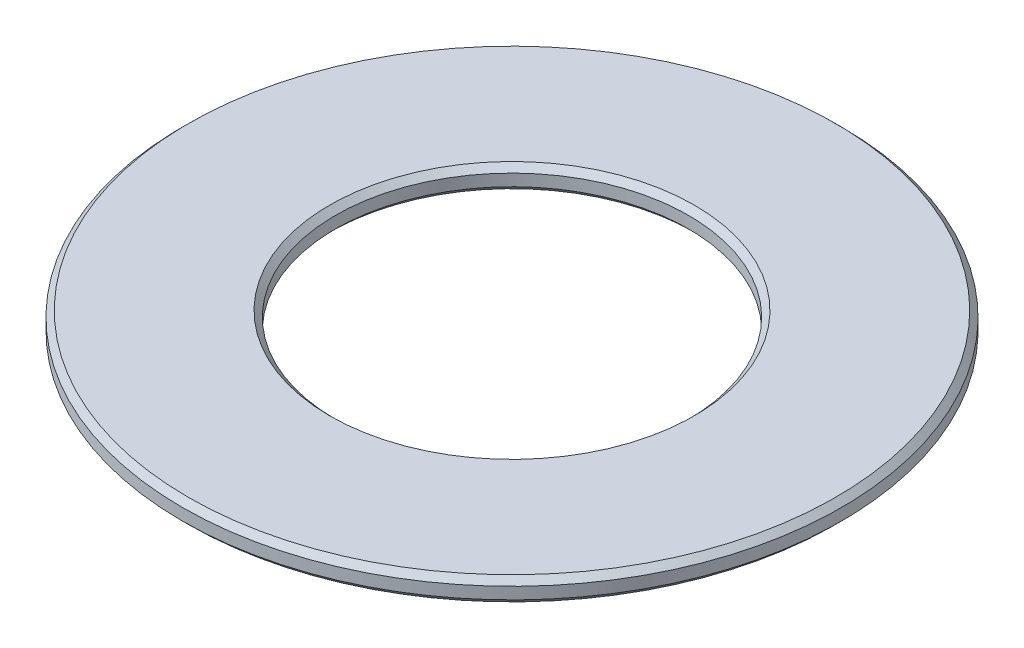
SolidWorks part; units mm, degrees
material "AISI Type A2 Tool Steel"
ref_plane "Front Plane" through (0, 0, 0) normal (0, 0, 1) x (1, 0, 0)
ref_plane "Top Plane" through (0, 0, 0) normal (0, 1, 0) x (1, 0, 0)
ref_plane "Right Plane" through (0, 0, 0) normal (1, 0, 0) x (0, 0, -1)
sketch "Sketch1" plane through (0, 0, 0) normal (0, 1, 0) x (1, 0, 0)
  circle A0 centre (0, 0) radius 14
  circle A1 centre (0, 0) radius 7.5
  dimension "D1" = 15
  dimension "D2" = 28
extrude "Boss-Extrude1" add sketch "Sketch1" along normal blind 1
chamfer "Chamfer1" distance 0.25 angle 45 4 edges at (0, 0, 14) (0, 1, 14) (0, 0, 7.5) (0, 1, 7.5)
